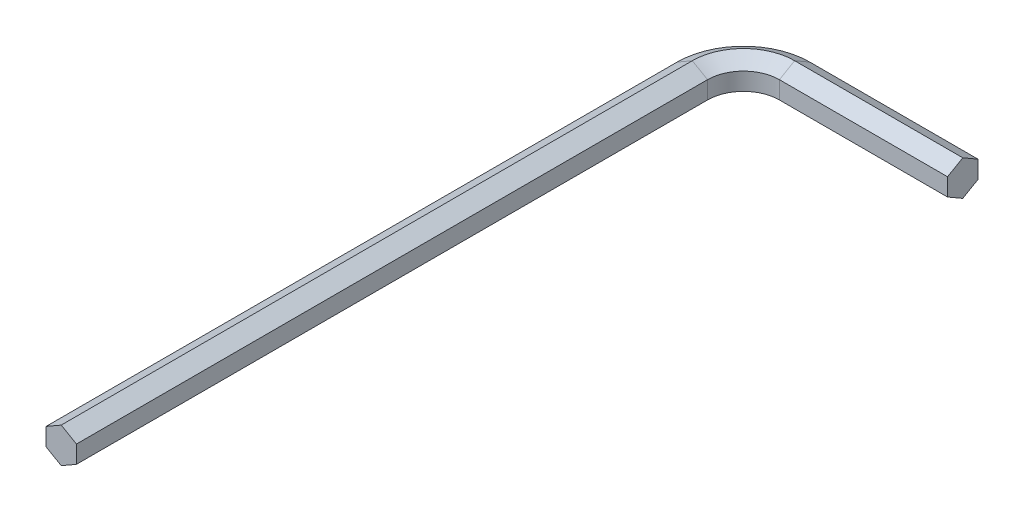
SolidWorks part; units mm, degrees
ref_plane "Front Plane" through (0, 0, 0) normal (0, 0, 1) x (1, 0, 0)
ref_plane "Top Plane" through (0, 0, 0) normal (0, 1, 0) x (1, 0, 0)
ref_plane "Right Plane" through (0, 0, 0) normal (1, 0, 0) x (0, 0, -1)
sketch "Sketch1" plane through (0, 0, 0) normal (0, 1, 0) x (1, 0, 0)
  line L0 (0, 0) -> (0, 51.8)
  line L1 (4.2, 56) -> (18, 56)
  arc A0 (0, 51.8) -> (4.2, 56) centre (4.2, 51.8) cw
  point P6 (0, 56)
  dimension "D3" = 4.2
  dimension "D1" = 18
  dimension "D2" = 56
sketch "Sketch2" plane through (0, 0, 0) normal (0, 0, 1) x (1, 0, 0)
  line L1 (0, -1.4434) -> (1.25, -0.7217)
  line L2 (1.25, -0.7217) -> (1.25, 0.7217)
  line L3 (1.25, 0.7217) -> (0, 1.4434)
  line L4 (0, 1.4434) -> (-1.25, 0.7217)
  line L5 (-1.25, 0.7217) -> (-1.25, -0.7217)
  line L6 (-1.25, -0.7217) -> (0, -1.4434)
  circle A0 centre (0, 0) radius 1.25 construction
  point P1 (0, 0)
  dimension "D1" = 2.5
sweep "Sweep1" add profiles "Sketch2" path "Sketch1"
